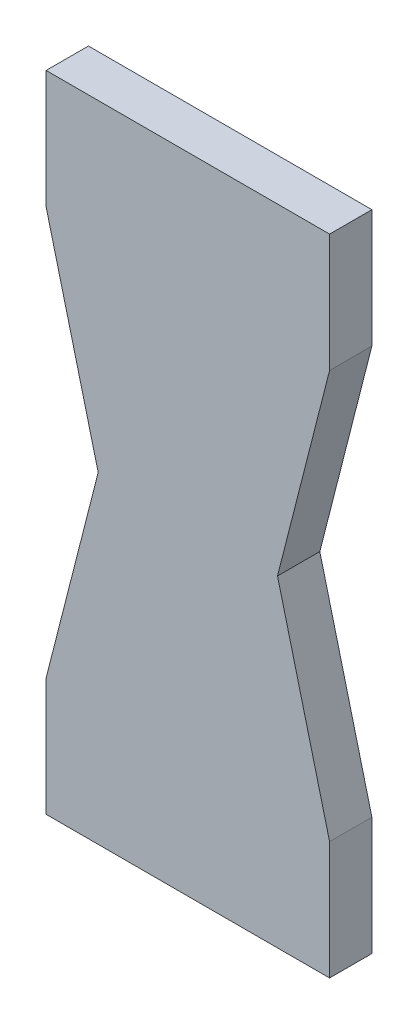
SolidWorks part; units mm, degrees
ref_plane "Piano frontale" through (0, 0, 0) normal (0, 0, 1) x (1, 0, 0)
ref_plane "Piano superiore" through (0, 0, 0) normal (0, 1, 0) x (1, 0, 0)
ref_plane "Piano destro" through (0, 0, 0) normal (1, 0, 0) x (0, 0, -1)
sketch "Schizzo1" plane through (0, 0, 0) normal (0, 0, 1) x (1, 0, 0)
  line L0 (10.2076, 24.7298) -> (23.4076, 24.7298) construction
  line L1 (10.2076, 39.7298) -> (23.4076, 39.7298)
  line L2 (10.2076, 39.7298) -> (10.2076, 9.7298)
  line L3 (10.2076, 9.7298) -> (23.4076, 9.7298)
  line L4 (23.4076, 39.7298) -> (23.4076, 9.7298)
  line L5 (12.6326, 24.7298) -> (10.2076, 34.2298)
  line L6 (16.8076, 39.7298) -> (16.8076, 9.7298) construction
  line L7 (12.6326, 24.7298) -> (10.2076, 15.2298)
  line L8 (20.9826, 24.7298) -> (23.4076, 15.2298)
  line L9 (20.9826, 24.7298) -> (23.4076, 34.2298)
  dimension "D1" = 30
  dimension "D2" = 13.2
  dimension "D3" = 8.35
  dimension "D4" = 5.5
extrude "Estrusione-Estrusione1" add sketch "Schizzo1" along normal blind 1.97 contours L8 L9 L4 L1 L2 L5 L7 L3
